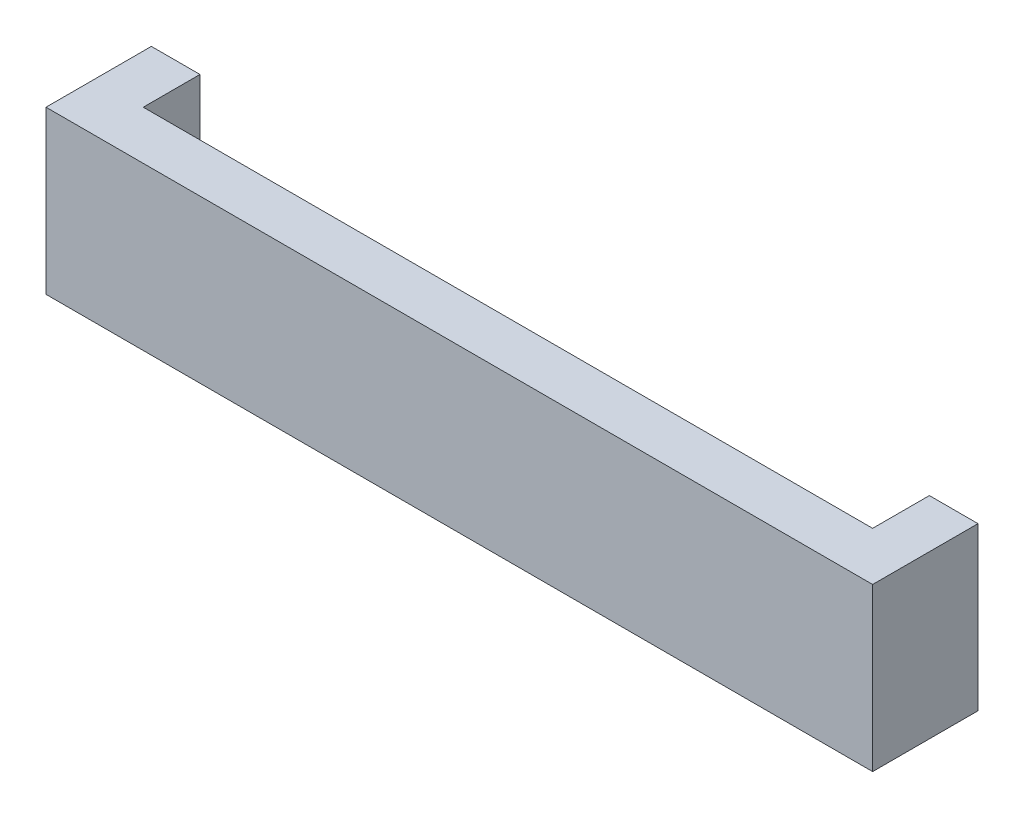
SolidWorks part; units mm, degrees
ref_plane "Front Plane" through (0, 0, 0) normal (0, 0, 1) x (1, 0, 0)
ref_plane "Top Plane" through (0, 0, 0) normal (0, 1, 0) x (1, 0, 0)
ref_plane "Right Plane" through (0, 0, 0) normal (1, 0, 0) x (0, 0, -1)
sketch "Sketch1" plane through (0, 0, 0) normal (0, 0, 1) x (1, 0, 0)
  line L1 (-25.5, -5) -> (25.5, -5)
  line L2 (-25.5, -5) -> (-25.5, 5)
  line L3 (-25.5, 5) -> (25.5, 5)
  line L4 (25.5, -5) -> (25.5, 5)
  line L5 (-25.5, -5) -> (25.5, 5) construction
  line L6 (-25.5, 5) -> (25.5, -5) construction
  point P0 (0, 0)
  dimension "D1" = 51
  dimension "D2" = 10
extrude "Boss-Extrude1" add sketch "Sketch1" along normal blind 6.5
sketch "Sketch2" plane through (0, -5, 0) normal (0, -1, 0) x (1, 0, 0)
  line L1 (-25.5, 0) -> (25.5, 0) construction
  line L2 (-22.5, 0) -> (-22.5, 3.5)
  line L3 (-22.5, 3.5) -> (22.5, 3.5)
  line L4 (22.5, 3.5) -> (22.5, 0)
  line L5 (22.5, 0) -> (-22.5, 0)
extrude "Cut-Extrude1" cut sketch "Sketch2" against normal blind 10
